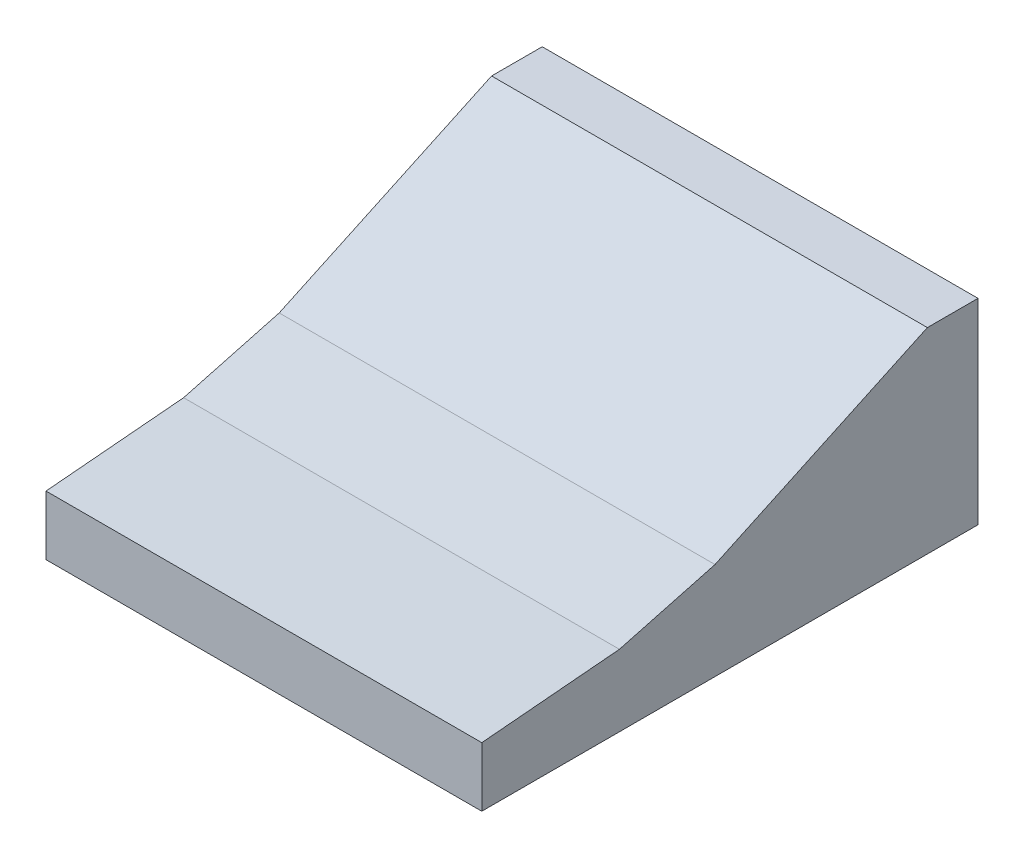
SolidWorks part; units mm, degrees
ref_plane "Ebene vorne" through (0, 0, 0) normal (0, 0, 1) x (1, 0, 0)
ref_plane "Ebene oben" through (0, 0, 0) normal (0, 1, 0) x (1, 0, 0)
ref_plane "Ebene rechts" through (0, 0, 0) normal (1, 0, 0) x (0, 0, -1)
sketch "Skizze1" plane through (0, 0, 0) normal (1, 0, 0) x (0, 0, -1)
  line L1 (138.9614, 72.1575) -> (235.4578, 98.0137)
  line L2 (235.4578, 98.0137) -> (449.8791, 198)
  line L3 (449.8791, 198) -> (501, 198)
  line L4 (501, 198) -> (501, 0)
  line L5 (501, 0) -> (0, 0)
  line L6 (0, 0) -> (0, 60)
  line L7 (0, 60) -> (138.9614, 72.1575)
  point P3 (122.8059, 38.1399)
  point P9 (49.2522, 13.8773)
  point P10 (75.71, 20.6324)
  point P11 (32.2108, 11.9877)
  point P12 (35.3628, 166.7614)
  point P13 (150.3879, 72.3882)
  point P14 (441.739, 198)
  point P15 (303.2956, 118.536)
  point P16 (282.9733, 106.459)
  point P17 (401.5172, 198)
  point P18 (428.6835, 198)
  point P19 (107.0193, 69.363)
  point P20 (448.1926, 198)
  point P21 (0, 0)
  point P22 (144.3581, 72.6297)
  point P23 (430.6878, 198)
  point P24 (249.0756, 101.6626)
  point P25 (430.6878, 198)
  dimension "D1" = 5
  dimension "D2" = 15
  dimension "D3" = 25
  dimension "D4" = 501
  dimension "D5" = 198
  dimension "D6" = 60
extrude "Aufsatz-Linear austragen1" add sketch "Skizze1" along normal blind 440
